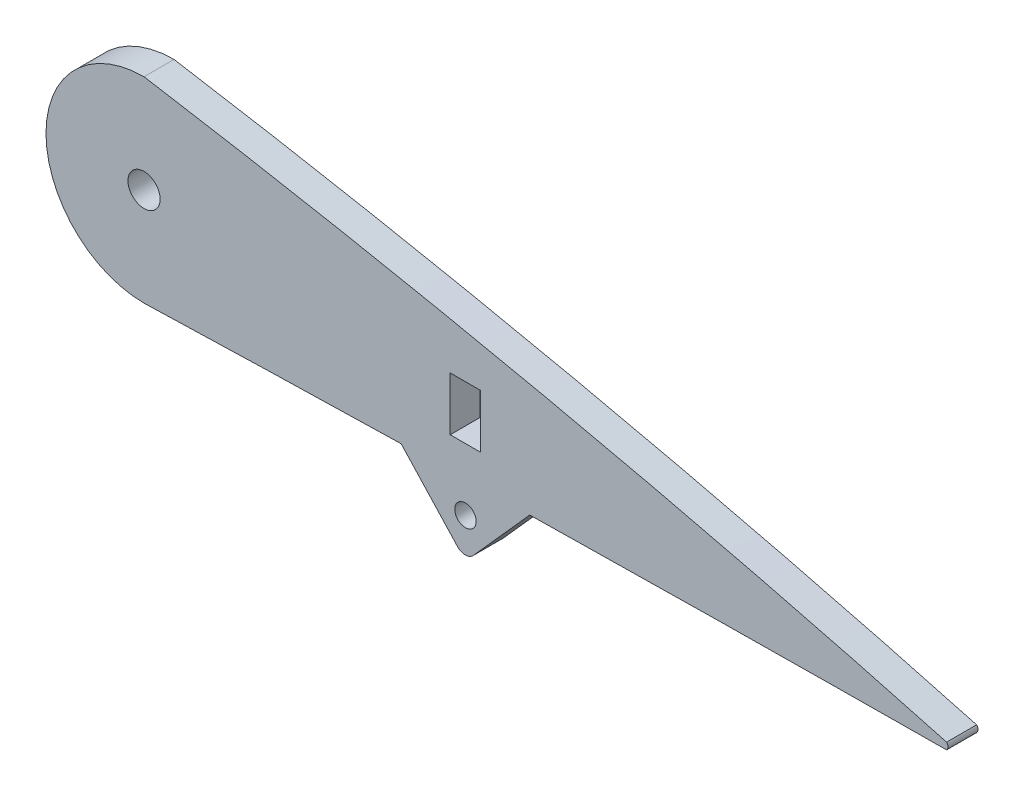
SolidWorks part; units mm, degrees
material "Фанера"
ref_plane "Front Plane" through (0, 0, 0) normal (0, 0, 1) x (1, 0, 0)
ref_plane "Top Plane" through (0, 0, 0) normal (0, 1, 0) x (1, 0, 0)
ref_plane "Right Plane" through (0, 0, 0) normal (1, 0, 0) x (0, 0, -1)
curve "Кривая5"
  spline degree 3 poles (0.048, 0.6214, 0) (0.0227, 0.3735, 0) (-0.0278, -0.1225, 0) (0.078, -0.8844, 0) (0.3497, -1.6388, 0) (0.8143, -2.3651, 0) (1.4635, -3.0393, 0) (2.291, -3.661, 0) (3.3059, -4.2358, 0) (4.5353, -4.7737, 0) (6.0297, -5.2822, 0) (7.869, -5.7653, 0) (10.1688, -6.2217, 0) (13.0754, -6.6396, 0) (16.7281, -6.993, 0) (21.19, -7.2473, 0) (26.4, -7.3766, 0) (32.1974, -7.3763, 0) (38.3978, -7.2614, 0) (44.8576, -7.0566, 0) (51.4865, -6.7865, 0) (58.231, -6.4723, 0) (65.0521, -6.1329, 0) (71.9108, -5.784, 0) (78.7714, -5.4397, 0) (85.6105, -5.111, 0) (92.4321, -4.805, 0) (99.255, -4.532, 0) (106.0974, -4.2783, 0) (112.9692, -4.0031, 0) (119.8644, -3.7232, 0) (126.7739, -3.4401, 0) (133.6816, -3.1587, 0) (140.5819, -2.8824, 0) (147.472, -2.6139, 0) (154.3526, -2.3556, 0) (161.225, -2.1094, 0) (168.0909, -1.8766, 0) (174.9516, -1.6586, 0) (181.8086, -1.4564, 0) (188.6632, -1.2704, 0) (195.5166, -1.1011, 0) (202.3695, -0.9486, 0) (209.2212, -0.8129, 0) (216.0668, -0.6936, 0) (222.8864, -0.5903, 0) (229.6176, -0.5029, 0) (236.0874, -0.4315, 0) (241.9808, -0.3765, 0) (246.559, -0.3395, 0) (249.1205, -0.3213, 0) (250, -0.315, 0) knots 0 0 0 0 0.002941 0.005884 0.009016 0.012365 0.016008 0.020037 0.024574 0.029784 0.035897 0.04324 0.052276 0.063635 0.077983 0.095698 0.11652 0.139661 0.164312 0.189919 0.216157 0.242838 0.269834 0.296993 0.324123 0.351139 0.378036 0.404946 0.431961 0.459078 0.486347 0.513641 0.540929 0.568176 0.59538 0.622543 0.649673 0.676775 0.703855 0.730919 0.757971 0.785018 0.812062 0.839103 0.866132 0.893099 0.919831 0.94581 0.969681 0.98959 1 1 1 1
curve "Кривая6"
  spline degree 3 poles (250, 0.315, 0) (249.1557, 0.545, 0) (246.7202, 1.2085, 0) (242.3913, 2.3583, 0) (236.8498, 3.7876, 0) (230.7799, 5.298, 0) (224.4559, 6.8129, 0) (218.0305, 8.2916, 0) (211.5624, 9.7197, 0) (205.0724, 11.0924, 0) (198.568, 12.4079, 0) (192.0524, 13.6653, 0) (185.5276, 14.8641, 0) (178.9953, 16.0034, 0) (172.4571, 17.0824, 0) (165.9143, 18.0998, 0) (159.3687, 19.0545, 0) (152.8218, 19.9449, 0) (146.2754, 20.7693, 0) (139.7314, 21.5257, 0) (133.1918, 22.212, 0) (126.6587, 22.8257, 0) (120.1368, 23.364, 0) (113.6286, 23.8247, 0) (107.1527, 24.2002, 0) (100.7411, 24.4984, 0) (94.4118, 24.6866, 0) (88.1559, 24.7401, 0) (81.949, 24.6588, 0) (75.7805, 24.441, 0) (69.6537, 24.0819, 0) (63.5754, 23.578, 0) (57.5552, 22.9249, 0) (51.6058, 22.1191, 0) (45.7444, 21.1566, 0) (39.9959, 20.0354, 0) (34.3979, 18.7563, 0) (29.0104, 17.3276, 0) (23.9258, 15.7719, 0) (19.2707, 14.1343, 0) (15.1791, 12.4833, 0) (11.7405, 10.8956, 0) (8.9594, 9.4296, 0) (6.7609, 8.1086, 0) (5.0337, 6.9246, 0) (3.6717, 5.8542, 0) (2.5921, 4.8713, 0) (1.7382, 3.9526, 0) (1.0699, 3.0809, 0) (0.5716, 2.2416, 0) (0.2158, 1.4308, 0) (0.1023, 0.8832, 0) (0.048, 0.6214, 0) knots 0 0 0 0 0.010162 0.029313 0.052012 0.076619 0.101948 0.127526 0.153184 0.178868 0.204558 0.230246 0.255926 0.281594 0.307246 0.332878 0.358485 0.384061 0.409603 0.435104 0.460559 0.485959 0.511303 0.536552 0.561723 0.586629 0.611085 0.635251 0.659272 0.683164 0.706922 0.730536 0.753983 0.777235 0.800246 0.822951 0.845237 0.866916 0.887662 0.906968 0.924203 0.938879 0.950932 0.960693 0.968647 0.975233 0.980795 0.985584 0.989782 0.993521 0.996902 1 1 1 1
sketch "Эскиз1" plane through (0, 0, 0) normal (0, 0, 1) x (1, 0, 0)
  line L0 (250.1305, 0) -> (250.1305, 54.8427) construction
  line L1 (0, 0) -> (0, 70.5199) construction
  line L2 (0, 0) -> (253.0634, 0) construction
  line L3 (62.5326, 62.6361) -> (62.5326, -41.5636) construction
  line L4 (142.5326, 67.9319) -> (142.5326, -57.0034) construction
  line L5 (175.0913, 63.8571) -> (175.0913, -32.3947) construction
  line L6 (32.5326, -14.3434) -> (32.5326, 29.5903) construction
  line L7 (165.9405, 18.0854) -> (165.9405, -1.9504)
  line L8 (199.0913, -1.0223) -> (204.3439, -6.6984)
  line L9 (203.6663, 6.9939) -> (206.5163, 6.9939)
  line L10 (203.6663, 6.9939) -> (203.6663, 1.9939)
  line L11 (203.6663, 1.9939) -> (206.5163, 1.9939)
  line L12 (206.5163, 6.9939) -> (206.5163, 1.9939)
  line L13 (203.6663, 6.9939) -> (206.5163, 1.9939) construction
  line L14 (203.6663, 1.9939) -> (206.5163, 6.9939) construction
  line L15 (205.824, -6.6849) -> (211.0913, -0.7814)
  line L16 (205.0913, 14.1754) -> (205.0913, -11.6971) construction
  arc A0 (250, 0.315) -> (250, -0.315) centre (249.685, 0) cw
  circle A1 centre (62.5326, 8.5962) radius 8.1
  circle A2 centre (142.5326, 8.5962) radius 5.1
  circle A3 centre (32.5326, 5.4481) radius 7
  circle A5 centre (102.5326, 8.5962) radius 9.5
  arc A6 (175.0913, -1.657) -> (175.0913, 16.6448) centre (175.0913, 7.4939) cw
  circle A7 centre (175.0913, 7.4939) radius 1.5
  arc A8 (204.3439, -6.6984) -> (205.824, -6.6849) centre (205.0778, -6.0192) ccw
  circle A9 centre (205.0913, -3.8061) radius 1
  spline S0 degree 3 poles (0.048, 0.6214) (0.0227, 0.3735) (-0.0278, -0.1225) (0.078, -0.8844) (0.3497, -1.6388) (0.8143, -2.3651) (1.4635, -3.0393) (2.291, -3.661) (3.3059, -4.2358) (4.5353, -4.7737) (6.0297, -5.2822) (7.869, -5.7653) (10.1688, -6.2217) (13.0754, -6.6396) (16.7281, -6.993) (21.19, -7.2473) (26.4, -7.3766) (32.1974, -7.3763) (38.3978, -7.2614) (44.8576, -7.0566) (51.4865, -6.7865) (58.231, -6.4723) (65.0521, -6.1329) (71.9108, -5.784) (78.7714, -5.4397) (85.6105, -5.111) (92.4321, -4.805) (99.255, -4.532) (106.0974, -4.2783) (112.9692, -4.0031) (119.8644, -3.7232) (126.7739, -3.4401) (133.6816, -3.1587) (140.5819, -2.8824) (147.472, -2.6139) (154.3526, -2.3556) (161.225, -2.1094) (168.0909, -1.8766) (174.9516, -1.6586) (181.8086, -1.4564) (188.6632, -1.2704) (195.5166, -1.1011) (202.3695, -0.9486) (211.4992, -0.7677) (220.6031, -0.6199) (229.6176, -0.5029) (236.0874, -0.4315) (241.9808, -0.3765) (246.559, -0.3395) (249.1205, -0.3213) (250, -0.315) knots 0 0 0 0 0.002941 0.005884 0.009016 0.012365 0.016008 0.020037 0.024574 0.029784 0.035897 0.04324 0.052276 0.063635 0.077983 0.095698 0.11652 0.139661 0.164312 0.189919 0.216157 0.242838 0.269834 0.296993 0.324123 0.351139 0.378036 0.404946 0.431961 0.459078 0.486347 0.513641 0.540929 0.568176 0.59538 0.622543 0.649673 0.676775 0.703855 0.730919 0.757971 0.785018 0.812062 0.839103 0.893099 0.919831 0.94581 0.969681 0.98959 1 1 1 1 construction
  spline S1 degree 3 poles (1021.8633, 1838.7787) (414.3615, -64.7736) (332.0293, -21.4512) (242.3913, 2.3583) (236.8498, 3.7876) (230.7799, 5.298) (224.4559, 6.8129) (218.0305, 8.2916) (211.5624, 9.7197) (205.0724, 11.0924) (198.568, 12.4079) (192.0524, 13.6653) (185.5276, 14.8641) (178.9953, 16.0034) (172.4571, 17.0824) (165.9143, 18.0998) (159.3687, 19.0545) (152.8218, 19.9449) (146.2754, 20.7693) (139.7314, 21.5257) (133.1918, 22.212) (126.6587, 22.8257) (120.1368, 23.364) (113.6286, 23.8247) (107.1527, 24.2002) (100.7411, 24.4984) (94.4118, 24.6866) (88.1559, 24.7401) (81.949, 24.6588) (75.7805, 24.441) (69.6537, 24.0819) (63.5754, 23.578) (57.5552, 22.9249) (51.6058, 22.1191) (45.7444, 21.1566) (39.9959, 20.0354) (34.3979, 18.7563) (29.0104, 17.3276) (23.9258, 15.7719) (19.2707, 14.1343) (15.1791, 12.4833) (11.7405, 10.8956) (8.9594, 9.4296) (6.7609, 8.1086) (5.0337, 6.9246) (3.6717, 5.8542) (2.5921, 4.8713) (1.7382, 3.9526) (1.0699, 3.0809) (0.5716, 2.2416) (-4.3308, -8.9285) (41.0506, -34.7699) (-1925.2597, 540.0689) knots -1.025 -1.025 -1.025 -1.025 0.010162 0.029313 0.052012 0.076619 0.101948 0.127526 0.153184 0.178868 0.204558 0.230246 0.255926 0.281594 0.307246 0.332878 0.358485 0.384061 0.409603 0.435104 0.460559 0.485959 0.511303 0.536552 0.561723 0.586629 0.611085 0.635251 0.659272 0.683164 0.706922 0.730536 0.753983 0.777235 0.800246 0.822951 0.845237 0.866916 0.887662 0.906968 0.924203 0.938879 0.950932 0.960693 0.968647 0.975233 0.980795 0.985584 0.989782 0.993521 0.996902 1.130551 1.130551 1.130551 1.130551 only from (250, 0.315) to (0.048, 0.6214) construction
  spline S2 degree 3 poles (0.048, 0.6214) (0.0227, 0.3735) (-0.0278, -0.1225) (0.078, -0.8844) (0.3497, -1.6388) (0.8143, -2.3651) (1.4635, -3.0393) (2.291, -3.661) (3.3059, -4.2358) (4.5353, -4.7737) (6.0297, -5.2822) (7.869, -5.7653) (10.1688, -6.2217) (13.0754, -6.6396) (16.7281, -6.993) (21.19, -7.2473) (26.4, -7.3766) (32.1974, -7.3763) (38.3978, -7.2614) (44.8576, -7.0566) (51.4865, -6.7865) (58.231, -6.4723) (65.0521, -6.1329) (71.9108, -5.784) (78.7714, -5.4397) (85.6105, -5.111) (92.4321, -4.805) (99.255, -4.532) (106.0974, -4.2783) (112.9692, -4.0031) (119.8644, -3.7232) (126.7739, -3.4401) (133.6816, -3.1587) (140.5819, -2.8824) (147.472, -2.6139) (154.3526, -2.3556) (161.225, -2.1094) (168.0909, -1.8766) (174.9516, -1.6586) (181.8086, -1.4564) (188.6632, -1.2704) (194.4239, -1.1281) (197.8998, -1.0487) (199.0913, -1.0223) knots 0 0 0 0 0.002941 0.005884 0.009016 0.012365 0.016008 0.020037 0.024574 0.029784 0.035897 0.04324 0.052276 0.063635 0.077983 0.095698 0.11652 0.139661 0.164312 0.189919 0.216157 0.242838 0.269834 0.296993 0.324123 0.351139 0.378036 0.404946 0.431961 0.459078 0.486347 0.513641 0.540929 0.568176 0.59538 0.622543 0.649673 0.676775 0.703855 0.730919 0.757971 0.785018 0.799124 0.799124 0.799124 0.799124
  spline S3 degree 3 poles (250, 0.315) (249.1557, 0.545) (246.7202, 1.2085) (242.3913, 2.3583) (236.8498, 3.7876) (230.7799, 5.298) (224.4559, 6.8129) (218.0305, 8.2916) (211.5624, 9.7197) (205.0724, 11.0924) (198.568, 12.4079) (192.0524, 13.6653) (185.5276, 14.8641) (178.9953, 16.0034) (172.4571, 17.0824) (165.9143, 18.0998) (159.3687, 19.0545) (152.8218, 19.9449) (146.2754, 20.7693) (139.7314, 21.5257) (133.1918, 22.212) (126.6587, 22.8257) (120.1368, 23.364) (113.6286, 23.8247) (107.1527, 24.2002) (100.7411, 24.4984) (94.4118, 24.6866) (88.1559, 24.7401) (81.949, 24.6588) (75.7805, 24.441) (69.6537, 24.0819) (63.5754, 23.578) (57.5552, 22.9249) (51.6058, 22.1191) (45.7444, 21.1566) (39.9959, 20.0354) (34.3979, 18.7563) (29.0104, 17.3276) (23.9258, 15.7719) (19.2707, 14.1343) (15.1791, 12.4833) (11.7405, 10.8956) (8.9594, 9.4296) (6.7609, 8.1086) (5.0337, 6.9246) (3.6717, 5.8542) (2.5921, 4.8713) (1.7382, 3.9526) (1.0699, 3.0809) (0.5716, 2.2416) (0.2158, 1.4308) (0.1023, 0.8832) (0.048, 0.6214) knots 0 0 0 0 0.010162 0.029313 0.052012 0.076619 0.101948 0.127526 0.153184 0.178868 0.204558 0.230246 0.255926 0.281594 0.307246 0.332878 0.358485 0.384061 0.409603 0.435104 0.460559 0.485959 0.511303 0.536552 0.561723 0.586629 0.611085 0.635251 0.659272 0.683164 0.706922 0.730536 0.753983 0.777235 0.800246 0.822951 0.845237 0.866916 0.887662 0.906968 0.924203 0.938879 0.950932 0.960693 0.968647 0.975233 0.980795 0.985584 0.989782 0.993521 0.996902 1 1 1 1
  spline S4 degree 3 poles (211.0913, -0.7814) (215.0296, -0.7106) (221.2261, -0.6119) (229.6176, -0.5029) (236.0874, -0.4315) (241.9808, -0.3765) (246.559, -0.3395) (249.1205, -0.3213) (250, -0.315) knots 0.846478 0.846478 0.846478 0.846478 0.893099 0.919831 0.94581 0.969681 0.98959 1 1 1 1
  point P22 (62.5326, 23.4501)
  point P23 (62.5326, -6.2577)
  point P26 (32.5326, 18.2506)
  point P27 (32.5326, -7.3543)
  point P30 (175.0913, 16.6448)
  point P31 (175.0913, -1.657)
  point P37 (205.0913, 4.4939)
  point P48 (205.0778, -3.9078)
  point P51 (205.0913, -7.5061)
  dimension "D3" = 16.2
  dimension "D8" = 14
  dimension "D10" = 10.2
  dimension "D9" = 19
  dimension "D15" = 9.1509
  dimension "D16" = 3
  dimension "D24" = 1
  dimension "D25" = 2
  dimension "D1" = 250.1305
  dimension "D2" = 62.5326
  dimension "D4" = 80
  dimension "D5" = 75.0391
  dimension "D6" = 29.7079
  dimension "D7" = 14.8539
  dimension "D11" = 40
  dimension "D12" = 30
  dimension "D13" = 25.6049
  dimension "D14" = 12.8025
  dimension "D17" = 2.85
  dimension "D18" = 5
  dimension "D19" = 30
  dimension "D20" = 3
  dimension "D21" = 6
  dimension "D22" = 6
  dimension "D23" = 12
  dimension "D26" = 8.3
extrude "Бобышка-Вытянуть1" add sketch "Эскиз1" along normal mid plane 2.8 contours A0 S3 A6 S2 A7
equation "\"D2@Эскиз1\"=\"D1@Эскиз1\"/4"
equation "\"D7@Эскиз1\"=\"D6@Эскиз1\"/2"
equation "\"D5@Эскиз1\"=\"D1@Эскиз1\"*0.3"
equation "\"D14@Эскиз1\"=\"D13@Эскиз1\"/2"
equation "\"t\"= 2.85"
